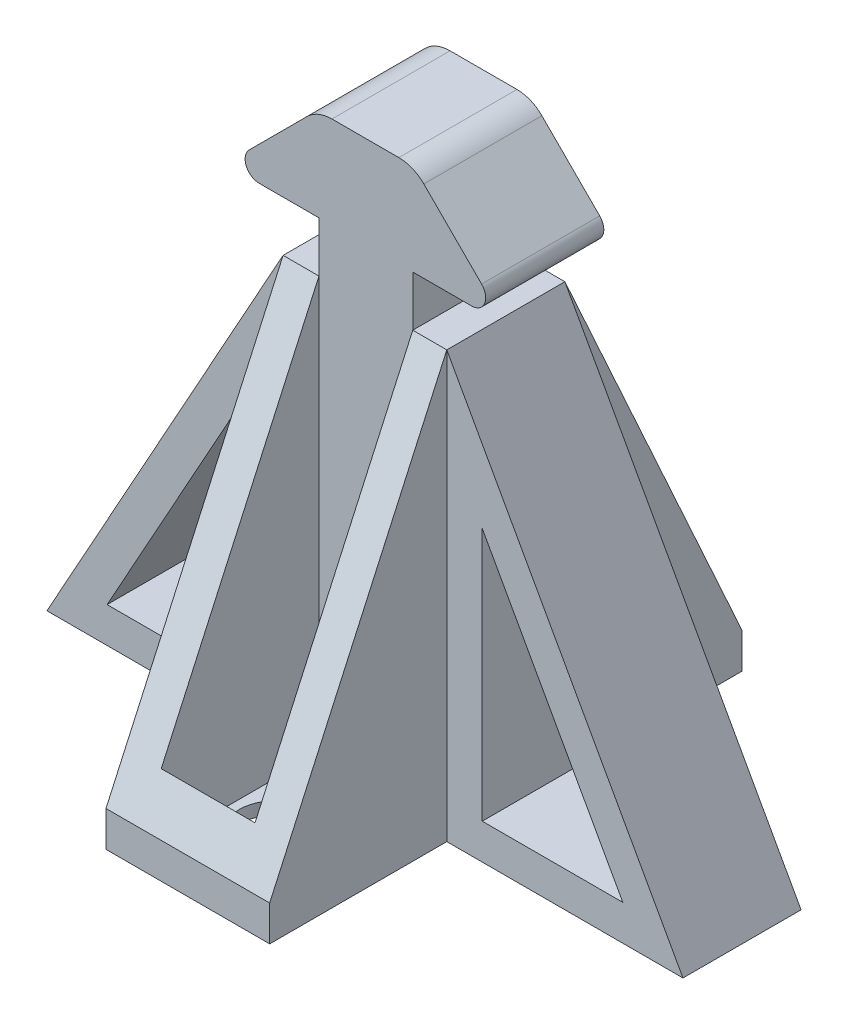
SolidWorks part; units mm, degrees
ref_plane "Front Plane" through (0, 0, 0) normal (0, 0, 1) x (1, 0, 0)
ref_plane "Top Plane" through (0, 0, 0) normal (0, 1, 0) x (1, 0, 0)
ref_plane "Right Plane" through (0, 0, 0) normal (1, 0, 0) x (0, 0, -1)
sketch "Sketch1" plane through (0, 0, 0) normal (0, 0, 1) x (1, 0, 0)
  line L0 (-113.4697, 674.107) -> (-113.4697, 674.0019) construction
  line L1 (-113.4697, 674.0019) -> (-110.4328, 674.0019) construction
  line L2 (-102.4905, 678.271) -> (-97.5028, 678.271)
  line L3 (-113.4697, 674.0019) -> (-110.4328, 674.0019)
  line L4 (-113.4697, 674.0019) -> (-113.4697, 640.5765)
  line L6 (-99.6065, 674.0019) -> (-99.6065, 637.935)
  line L7 (-111.1889, 637.935) -> (-111.1305, 637.935)
  line L8 (-112.2903, 678.271) -> (-110.4328, 678.271)
  line L11 (-110.4328, 678.271) -> (-110.4328, 674.0019)
  line L12 (-111.4436, 685.1974) -> (-116.3373, 680.3036)
  line L13 (-115.4954, 678.271) -> (-112.2903, 678.271)
  line L14 (-96.6608, 680.3036) -> (-101.5546, 685.1974)
  line L15 (-103.6661, 686.072) -> (-109.3321, 686.072)
  line L17 (-102.4905, 678.271) -> (-102.4905, 674.0019)
  line L19 (-102.4905, 674.0019) -> (-99.6065, 674.0019)
  line L20 (-99.6065, 637.935) -> (-113.4697, 637.935)
  line L21 (-111.1889, 637.935) -> (-111.1305, 637.935)
  line L22 (-99.6065, 640.5765) -> (-99.6065, 637.935)
  line L23 (-113.4697, 637.935) -> (-113.4697, 640.5765)
  line L26 (-111.1889, 637.935) -> (-111.1305, 637.935)
  line L27 (-99.6065, 640.5765) -> (-99.6065, 637.935)
  arc A12 (-109.3321, 686.072) -> (-111.4436, 685.1974) centre (-109.3321, 683.0859) ccw
  arc A13 (-116.3373, 680.3036) -> (-115.4954, 678.271) centre (-115.4954, 679.4617) ccw
  arc A14 (-97.5028, 678.271) -> (-96.6608, 680.3036) centre (-97.5028, 679.4617) ccw
  arc A15 (-101.5546, 685.1974) -> (-103.6661, 686.072) centre (-103.6661, 683.0859) ccw
extrude "Boss-Extrude1" add sketch "Sketch1" against normal blind 10 contours L6 L19 L17 L2 A14 L14 A15 L15 A12 L12 A13 L13 L8 L11 L3 L4 L23 L20
sketch "Sketch2" plane through (0, 0, 0) normal (0, 0, 1) x (1, 0, 0)
  line L0 (-113.4697, 674.0019) -> (-113.4697, 637.935) construction
  line L1 (-113.4697, 637.935) -> (-99.6065, 637.935)
  line L2 (-113.4697, 637.935) -> (-113.4697, 640.5756)
  line L3 (-113.4697, 640.5756) -> (-99.6065, 640.5756)
  line L4 (-99.6065, 637.935) -> (-99.6065, 640.5756)
  line L5 (-99.6065, 674.0019) -> (-99.6065, 637.935) construction
  dimension "D1" = 2.6406
extrude "Boss-Extrude2" add sketch "Sketch2" along normal blind 15 and the other way blind 25
sketch "Sketch3" plane through (0, 640.5756, 0) normal (0, 1, 0) x (1, 0, 0)
  line L0 (-106.5381, -15) -> (-106.4991, 0) construction
  line L1 (-99.6065, -15) -> (-113.4697, -15) construction
  line L2 (-103.6661, 0) -> (-109.3321, 0) construction
  line L3 (-99.6065, -7.5) -> (-113.4697, -7.5) construction
  line L4 (-99.6065, -15) -> (-99.6065, 0) construction
  line L5 (-113.4697, -15) -> (-113.4697, 0) construction
  circle A0 centre (-106.5381, -7.5) radius 3.15
extrude "Cut-Extrude1" cut sketch "Sketch3" against normal blind 2.65
sketch "Sketch4" plane through (0, 0, -10) normal (0, 0, -1) x (-1, 0, 0)
  line L0 (99.6065, 637.935) -> (79.6065, 637.935)
  line L1 (79.6065, 637.935) -> (99.6065, 674.0019)
  line L2 (99.6065, 674.0019) -> (99.6065, 637.935)
  line L3 (84.7005, 640.935) -> (96.6065, 662.4057)
  line L4 (96.6065, 662.4057) -> (96.6065, 640.935)
  line L5 (96.6065, 640.935) -> (84.7005, 640.935)
  line L6 (113.4697, 637.935) -> (133.4697, 637.935)
  line L7 (133.4697, 637.935) -> (113.4697, 674.0019)
  line L8 (113.4697, 674.0019) -> (113.4697, 637.935)
  line L9 (116.4697, 662.4057) -> (116.4697, 640.935)
  line L10 (116.4697, 640.935) -> (128.3758, 640.935)
  line L11 (128.3758, 640.935) -> (116.4697, 662.4057)
  dimension "D1" = 41.241
  dimension "D3" = 41.241
  dimension "D2" = 3
  dimension "D4" = 3
extrude "Boss-Extrude3" add sketch "Sketch4" against normal blind 10 contours L5 L4 L3 | L10 L11 L9 | L1 L2 L0 | L7 L8 L6
sketch "Sketch5" plane through (0, 640.5756, 0) normal (0, 1, 0) x (1, 0, 0)
  line L0 (-106.5381, 25) -> (-106.5381, 10) construction
  line L1 (-99.6065, 25) -> (-113.4697, 25) construction
  line L2 (-99.6065, 10) -> (-113.4697, 10) construction
  line L3 (-106.5381, 10) -> (-113.4697, 17.5) construction
  line L4 (-113.4697, 25) -> (-113.4697, 10) construction
  line L5 (-113.4697, 17.5) -> (-99.6065, 17.5) construction
  line L6 (-99.6065, 25) -> (-99.6065, 10) construction
  circle A0 centre (-106.5381, 17.5) radius 3.15
extrude "Cut-Extrude2" cut sketch "Sketch5" against normal blind 10 contours A0
sketch "Sketch6" plane through (0, 0, -10) normal (0, 0, -1) x (-1, 0, 0)
  line L0 (99.6065, 674.0019) -> (113.4697, 674.0019) construction
  line L1 (106.5381, 674.0019) -> (106.5381, 655.0019) construction
sketch "Sketch7" plane through (0, 0, -10) normal (0, 0, -1) x (-1, 0, 0)
  line L1 (99.6065, 640.5756) -> (113.4697, 640.5756)
  line L2 (99.6065, 640.5756) -> (99.6065, 674.0019)
  line L3 (99.6065, 674.0019) -> (113.4697, 674.0019)
  line L4 (113.4697, 640.5756) -> (113.4697, 674.0019)
extrude "Boss-Extrude4" add sketch "Sketch7" along normal blind 15 and the other way blind 25
sketch "Sketch10" plane through (-99.6065, 0, 0) normal (1, 0, 0) x (0, 0, -1)
  line L0 (-15, 637.935) -> (-15, 640.935) construction
  line L1 (-15, 637.935) -> (-15, 674.0019) construction
  line L2 (-15, 640.935) -> (25, 640.935) construction
  line L3 (25, 637.935) -> (25, 674.0019) construction
  line L4 (-15, 640.935) -> (0, 674.0019)
  line L5 (0, 674.0019) -> (-15, 674.0019)
  line L6 (-15, 674.0019) -> (-15, 640.935)
  line L7 (25, 640.935) -> (25, 674.0019)
  line L8 (25, 674.0019) -> (10, 674.0019)
  line L9 (10, 674.0019) -> (25, 640.935)
extrude "Cut-Extrude3" cut sketch "Sketch10" against normal blind 15 contours L8 L9 L7 | L4 L5 L6
sketch "Sketch13" plane through (0, 674.0019, 0) normal (0, 1, 0) x (1, 0, 0)
  line L0 (-110.4328, 10) -> (-102.4905, 10) construction
  line L2 (-110.4328, 10) -> (-102.4905, 10)
  line L3 (-110.4328, 10) -> (-110.4328, 23.0798)
  line L4 (-110.4328, 23.0798) -> (-102.4905, 23.0798)
  line L5 (-102.4905, 10) -> (-102.4905, 23.0798)
  line L6 (-110.4328, 0) -> (-102.4905, 0)
  line L7 (-110.4328, 0) -> (-110.4328, -13.3584)
  line L8 (-110.4328, -13.3584) -> (-102.4905, -13.3584)
  line L9 (-102.4905, 0) -> (-102.4905, -13.3584)
extrude "Cut-Extrude4" cut sketch "Sketch13" against normal blind 35 contours L9 L6 L7 L8 | L4 L5 L2 L3
